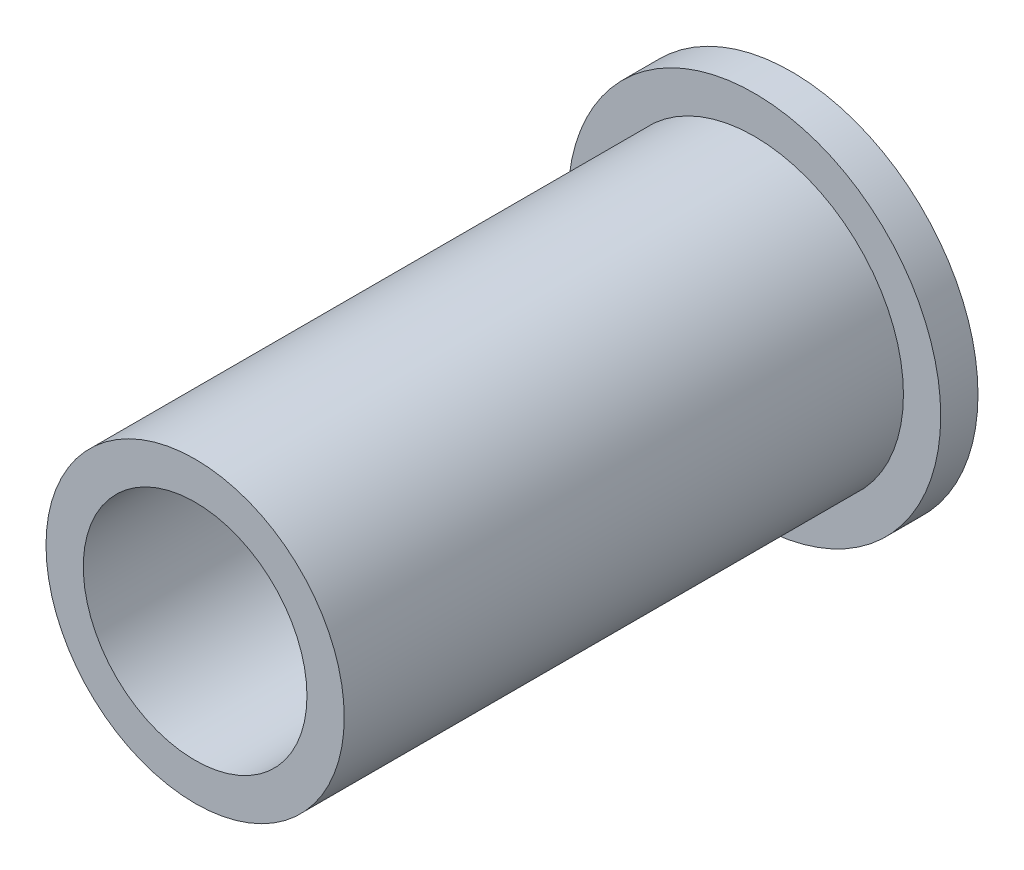
SolidWorks part; units mm, degrees
ref_plane "Front Plane" through (0, 0, 0) normal (0, 0, 1) x (1, 0, 0)
ref_plane "Top Plane" through (0, 0, 0) normal (0, 1, 0) x (1, 0, 0)
ref_plane "Right Plane" through (0, 0, 0) normal (1, 0, 0) x (0, 0, -1)
sketch "Sketch1" plane through (0, 0, 0) normal (0, 0, 1) x (1, 0, 0)
  circle A0 centre (0, 0) radius 25
  point P3 (0, 0)
  dimension "D1" = 50
extrude "Boss-Extrude1" add sketch "Sketch1" along normal blind 5
sketch "Sketch2" plane through (0, 0, 5) normal (0, 0, 1) x (1, 0, 0)
  circle A0 centre (0, 0) radius 20
  dimension "D1" = 40
extrude "Boss-Extrude2" add sketch "Sketch2" along normal blind 75
sketch "Sketch3" plane through (0, 0, 80) normal (0, 0, 1) x (1, 0, 0)
  circle A0 centre (0, 0) radius 15
  dimension "D1" = 30
extrude "Cut-Extrude1" cut sketch "Sketch3" against normal blind 70
